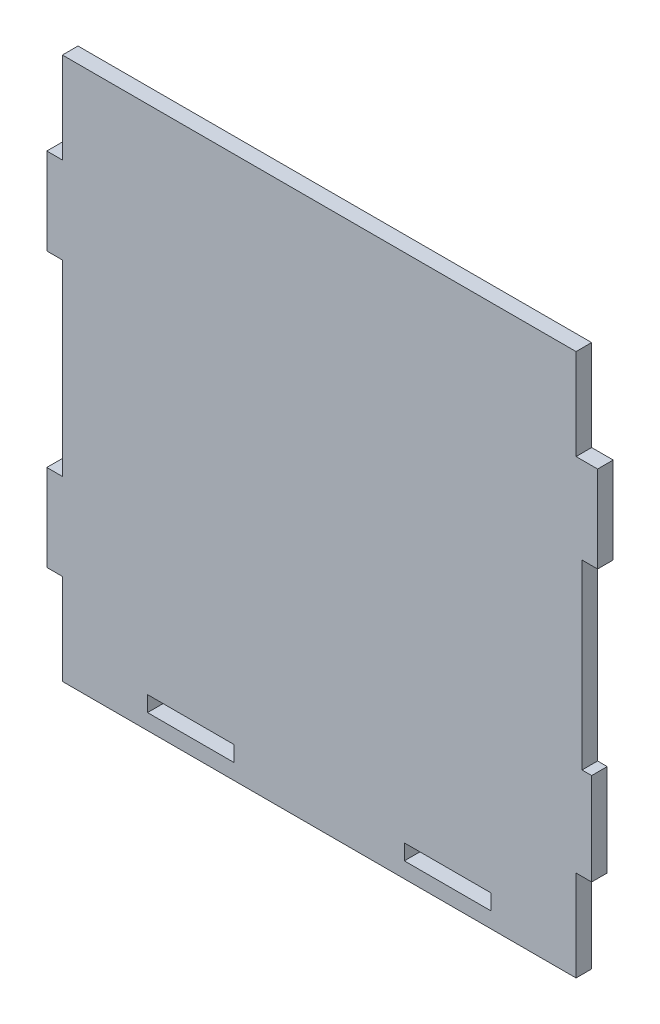
SolidWorks part; units mm, degrees
ref_plane "Front Plane" through (0, 0, 0) normal (0, 0, 1) x (1, 0, 0)
ref_plane "Top Plane" through (0, 0, 0) normal (0, 1, 0) x (1, 0, 0)
ref_plane "Right Plane" through (0, 0, 0) normal (1, 0, 0) x (0, 0, -1)
sketch "Sketch1" plane through (0, 0, 0) normal (0, 0, 1) x (1, 0, 0)
  line L0 (-204.0942, -205) -> (-204.0942, -415)
  line L1 (-210.9718, 0) -> (-804.0942, 0)
  line L2 (-804.0942, 0) -> (-804.0942, -105)
  line L3 (-804.0942, -105) -> (-822.0942, -105)
  line L4 (-822.0942, -105) -> (-822.0942, -205)
  line L5 (-822.0942, -205) -> (-804.0942, -205)
  line L6 (-804.0942, -205) -> (-804.0942, -421.4507)
  line L12 (-186.0942, -205) -> (-204.0942, -205)
  line L13 (-186.0942, -105) -> (-186.0942, -205)
  line L14 (-210.9718, -105) -> (-186.0942, -105)
  line L15 (-210.9718, 0) -> (-210.9718, -105)
  line L16 (-309.2524, -590.4507) -> (-309.2524, -608.4507)
  line L17 (-210.9718, -626.4507) -> (-210.9718, -521.4507)
  line L18 (-210.9718, -521.4507) -> (-192.9718, -521.4507)
  line L19 (-192.9718, -521.4507) -> (-192.9718, -415)
  line L20 (-192.9718, -415) -> (-204.0942, -415)
  line L21 (-822.0942, -421.4507) -> (-804.0942, -421.4507)
  line L22 (-822.0942, -521.4507) -> (-822.0942, -421.4507)
  line L23 (-804.0942, -521.4507) -> (-822.0942, -521.4507)
  line L24 (-804.0942, -626.4507) -> (-804.0942, -521.4507)
  line L25 (-210.9718, -626.4507) -> (-804.0942, -626.4507)
  line L26 (-705.8136, -590.4507) -> (-605.8136, -590.4507)
  line L27 (-705.8136, -590.4507) -> (-705.8136, -608.4507)
  line L28 (-705.8136, -608.4507) -> (-605.8136, -608.4507)
  line L29 (-605.8136, -590.4507) -> (-605.8136, -608.4507)
  line L32 (-309.2524, -590.4507) -> (-409.2524, -590.4507)
  line L33 (-309.2524, -608.4507) -> (-409.2524, -608.4507)
  line L34 (-409.2524, -590.4507) -> (-409.2524, -608.4507)
  point P10 (-655.8136, -599.4507)
  point P28 (-204.0942, -310)
  dimension "D1" = 18
  dimension "D2" = 105
  dimension "D3" = 18
  dimension "D4" = 18
  dimension "D5" = 100
  dimension "D6" = 100
  dimension "D7" = 18
extrude "Boss-Extrude1" add sketch "Sketch1" along normal blind 18
